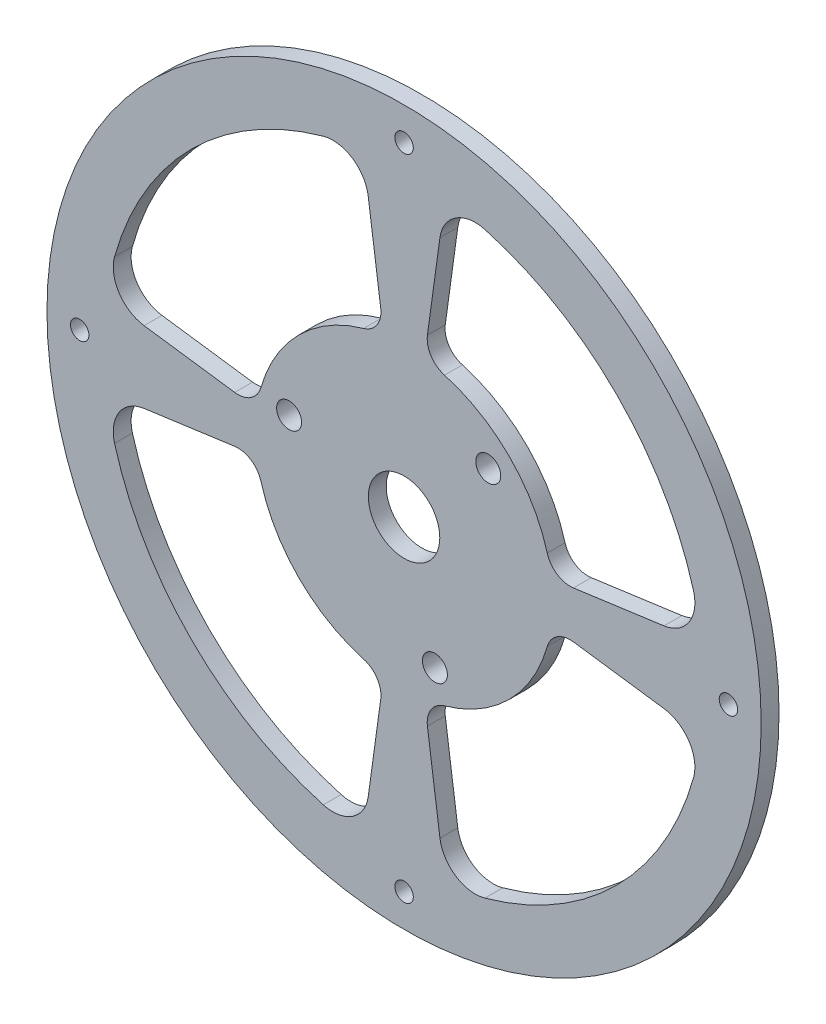
SolidWorks part; units mm, degrees
ref_plane "前视基准面" through (0, 0, 0) normal (0, 0, 1) x (1, 0, 0)
ref_plane "上视基准面" through (0, 0, 0) normal (0, 1, 0) x (1, 0, 0)
ref_plane "右视基准面" through (0, 0, 0) normal (1, 0, 0) x (0, 0, -1)
sketch "草图1" plane through (0, 0, 0) normal (0, 0, 1) x (1, 0, 0)
  line L0 (0, 0) -> (14.1421, 14.1421) construction
  line L1 (3.9232, -28.4536) -> (6.0227, -43.6804)
  line L2 (28.4536, 3.9232) -> (43.6804, 6.0227)
  line L3 (3.9232, 28.4536) -> (6.0227, 43.6804)
  line L4 (28.4536, -3.9232) -> (43.6804, -6.0227)
  line L5 (-28.4536, -3.9232) -> (-43.6804, -6.0227)
  line L6 (-3.9232, -28.4536) -> (-6.0227, -43.6804)
  line L7 (-3.9232, 28.4536) -> (-6.0227, 43.6804)
  line L8 (-28.4536, 3.9232) -> (-43.6804, 6.0227)
  circle A0 centre (0, 0) radius 60
  circle A1 centre (0, 54.5) radius 1.55
  circle A2 centre (-54.5, 0) radius 1.55
  circle A3 centre (0, -54.5) radius 1.55
  circle A4 centre (54.5, 0) radius 1.55
  arc A5 (48.6399, 13.5799) -> (13.5799, 48.6399) centre (0, 0) ccw
  circle A6 centre (0, 0) radius 20 construction
  circle A7 centre (14.1421, 14.1421) radius 2.1
  circle A8 centre (5.1764, -19.3185) radius 2.1
  circle A9 centre (-19.3185, 5.1764) radius 2.1
  circle A10 centre (0, 0) radius 6
  arc A11 (24.058, 6.798) -> (6.798, 24.058) centre (0, 0) ccw
  arc A12 (13.5799, 48.6399) -> (6.0227, 43.6804) centre (11.9665, 42.8609) ccw
  arc A13 (48.6399, 13.5799) -> (43.6804, 6.0227) centre (42.8609, 11.9665) cw
  arc A14 (3.9232, 28.4536) -> (6.798, 24.058) centre (7.8857, 27.9073) ccw
  arc A15 (28.4536, 3.9232) -> (24.058, 6.798) centre (27.9073, 7.8857) cw
  arc A16 (28.4536, -3.9232) -> (24.058, -6.798) centre (27.9073, -7.8857) ccw
  arc A17 (6.798, -24.058) -> (24.058, -6.798) centre (0, 0) ccw
  arc A18 (3.9232, -28.4536) -> (6.798, -24.058) centre (7.8857, -27.9073) cw
  arc A19 (13.5799, -48.6399) -> (6.0227, -43.6804) centre (11.9665, -42.8609) cw
  arc A20 (13.5799, -48.6399) -> (48.6399, -13.5799) centre (0, 0) ccw
  arc A21 (48.6399, -13.5799) -> (43.6804, -6.0227) centre (42.8609, -11.9665) ccw
  arc A22 (-3.9232, -28.4536) -> (-6.798, -24.058) centre (-7.8857, -27.9073) ccw
  arc A23 (-24.058, -6.798) -> (-6.798, -24.058) centre (0, 0) ccw
  arc A24 (-28.4536, -3.9232) -> (-24.058, -6.798) centre (-27.9073, -7.8857) cw
  arc A25 (-48.6399, -13.5799) -> (-43.6804, -6.0227) centre (-42.8609, -11.9665) cw
  arc A26 (-48.6399, -13.5799) -> (-13.5799, -48.6399) centre (0, 0) ccw
  arc A27 (-13.5799, -48.6399) -> (-6.0227, -43.6804) centre (-11.9665, -42.8609) ccw
  arc A28 (-28.4536, 3.9232) -> (-24.058, 6.798) centre (-27.9073, 7.8857) ccw
  arc A29 (-6.798, 24.058) -> (-24.058, 6.798) centre (0, 0) ccw
  arc A30 (-3.9232, 28.4536) -> (-6.798, 24.058) centre (-7.8857, 27.9073) cw
  arc A31 (-13.5799, 48.6399) -> (-6.0227, 43.6804) centre (-11.9665, 42.8609) cw
  arc A32 (-13.5799, 48.6399) -> (-48.6399, 13.5799) centre (0, 0) ccw
  arc A33 (-48.6399, 13.5799) -> (-43.6804, 6.0227) centre (-42.8609, 11.9665) ccw
  point P20 (0, 0)
  point P70 (0, 0)
  dimension "D1" = 3
  dimension "D2" = 4
extrude "凸台-拉伸1" add sketch "草图1" along normal blind 3
